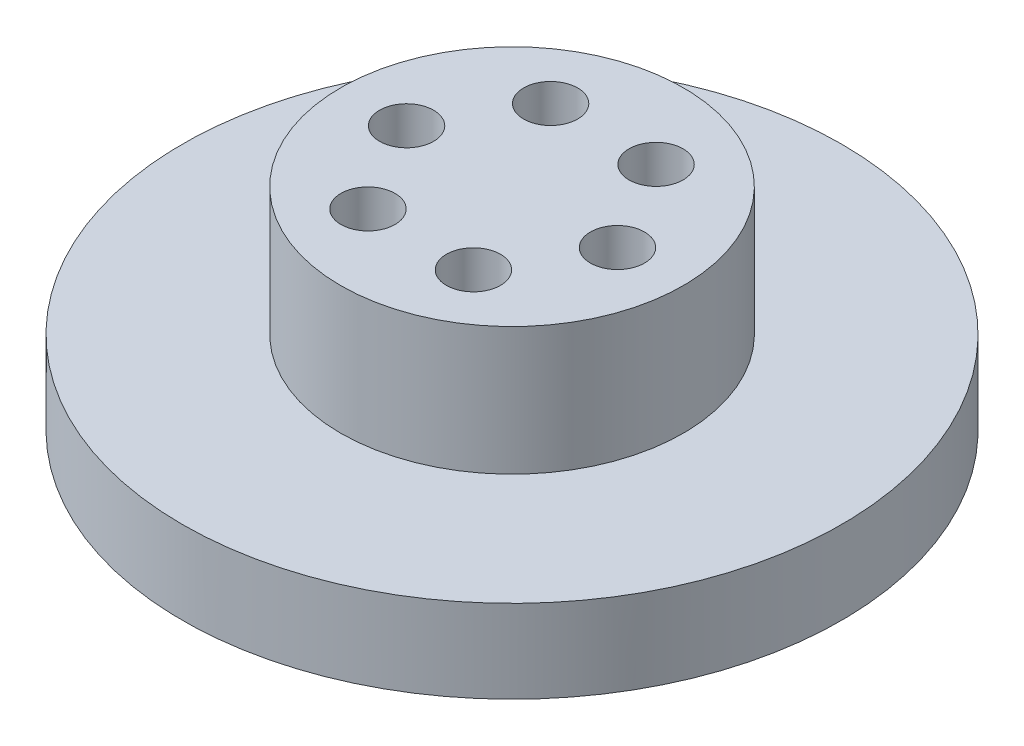
SolidWorks part; units mm, degrees
ref_plane "Front Plane" through (0, 0, 0) normal (0, 0, 1) x (1, 0, 0)
ref_plane "Top Plane" through (0, 0, 0) normal (0, 1, 0) x (1, 0, 0)
ref_plane "Right Plane" through (0, 0, 0) normal (1, 0, 0) x (0, 0, -1)
sketch "Sketch1" plane through (0, 0, 0) normal (0, 1, 0) x (1, 0, 0)
  circle A0 centre (0, 0) radius 16
  circle A2 centre (0, 0) radius 25
  circle A3 centre (16, 0) radius 3.75
  dimension "D1" = 32
  dimension "D3" = 50
  dimension "D4" = 7.5
extrude "Boss-Extrude1" add sketch "Sketch1" along normal blind 8 contours A2
sketch "Sketch2" plane through (0, 8, 0) normal (0, 1, 0) x (1, 0, 0)
  circle A0 centre (0, 0) radius 8
  circle A1 centre (8, 0) radius 2.05
  dimension "D1" = 16
  dimension "D2" = 4.1
extrude "Cut-Extrude3" cut sketch "Sketch2" against normal blind 7 contours A1
pattern_circular "CirPattern2" count 6 over 360 about axis through (0, 0, 0) along (0, 1, 0) of "Cut-Extrude3"
sketch "Sketch3" plane through (0, 0, 0) normal (0, 0, 1) x (1, 0, 0)
  line L0 (25, 6) -> (13, 6)
  line L2 (13, 6) -> (13, 8)
  line L3 (25, 8) -> (-25, 8) construction
  line L4 (13, 8) -> (25, 8)
  line L5 (25, 8) -> (25, 6)
  dimension "D1" = 2
  dimension "D2" = 12
ref_axis "Axis1" through (0, 10.5, 0) along (0, -1, 0)
revolve "Cut-Revolve1" cut sketch "Sketch3" angle 360 about axis through (0, 10.5, 0) along (0, -1, 0)
sketch "Sketch4" plane through (0, 0, 0) normal (0, -1, 0) x (1, 0, 0)
  circle A1 centre (0, 0) radius 25
  circle A2 centre (0, 0) radius 25
  dimension "D1" = 0
extrude "Cut-Extrude4" cut sketch "Sketch4" against normal blind 0.2
sketch "Sketch5" plane through (0, 8, 0) normal (0, 1, 0) x (1, 0, 0)
  circle A0 centre (4, 6.9282) radius 2.05 construction
  circle A1 centre (0, 0) radius 13
  circle A3 centre (8, 0) radius 2.05 construction
  circle A4 centre (4, -6.9282) radius 2.05 construction
  circle A5 centre (-4, -6.9282) radius 2.05 construction
  circle A6 centre (-8, 0) radius 2.05 construction
  circle A7 centre (-4, 6.9282) radius 2.05 construction
  circle A8 centre (4, 6.9282) radius 2.05
  circle A9 centre (8, 0) radius 2.05
  circle A10 centre (4, -6.9282) radius 2.05
  circle A11 centre (-4, -6.9282) radius 2.05
  circle A12 centre (-8, 0) radius 2.05
  circle A13 centre (-4, 6.9282) radius 2.05
  circle A15 centre (0, 0) radius 13
  dimension "D1" = 0
extrude "Boss-Extrude2" add sketch "Sketch5" along normal blind 2.2
sketch "Sketch6" plane through (0, 0.2, 0) normal (0, -1, 0) x (1, 0, 0)
  circle A0 centre (0, 0) radius 3.5
  dimension "D1" = 7
extrude "Cut-Extrude5" cut sketch "Sketch6" against normal blind 9
sketch "Sketch8" plane through (0, 10.2, 0) normal (0, 1, 0) x (1, 0, 0)
  circle A1 centre (4, 6.9282) radius 2.05
  circle A2 centre (4, 6.9282) radius 2.05
  circle A3 centre (8, 0) radius 2.05
  circle A4 centre (8, 0) radius 2.05
  circle A5 centre (4, -6.9282) radius 2.05
  circle A6 centre (4, -6.9282) radius 2.05
  circle A7 centre (-4, -6.9282) radius 2.05
  circle A8 centre (-4, -6.9282) radius 2.05
  circle A9 centre (-8, 0) radius 2.05
  circle A10 centre (-8, 0) radius 2.05
  circle A11 centre (-4, 6.9282) radius 2.05
  circle A12 centre (-4, 6.9282) radius 2.05
  circle M7 centre (-8, 0) radius 2.05
  circle M8 centre (4, -6.9282) radius 2.05
  circle M9 centre (4, 6.9282) radius 2.05
  circle M10 centre (0, 0) radius 13
  circle M11 centre (8, 0) radius 2.05
  circle M12 centre (-4, -6.9282) radius 2.05
  circle M13 centre (-4, 6.9282) radius 2.05
  dimension "D1" = 0
  dimension "D2" = 0
  dimension "D3" = 0
  dimension "D4" = 0
  dimension "D5" = 0
  dimension "D6" = 0
extrude "Boss-Extrude4" add sketch "Sketch8" along normal blind 3 contours M10 M8 M12 M13 M11 M9 M7
sketch "Sketch9" plane through (0, 0.2, 0) normal (0, -1, 0) x (1, 0, 0)
  circle A0 centre (16, 0) radius 3.6
  dimension "D1" = 7.2
  dimension "D2" = 16
extrude "Cut-Extrude6" cut sketch "Sketch9" against normal blind 4 contours A0
pattern_circular "CirPattern3" count 8 over 360 about axis through (0, 0, 0) along (0, 1, 0) of "Cut-Extrude6"
sketch "Sketch11" plane through (0, 0.2, 0) normal (0, -1, 0) x (1, 0, 0)
  circle A0 centre (-16, 0) radius 3.6 construction
  circle A1 centre (-11.3137, -11.3137) radius 3.6 construction
  circle A2 centre (0, -16) radius 3.6 construction
  circle A3 centre (11.3137, -11.3137) radius 3.6 construction
  circle A4 centre (0, 0) radius 3.5 construction
  circle A5 centre (16, 0) radius 3.6 construction
  circle A6 centre (11.3137, 11.3137) radius 3.6 construction
  circle A7 centre (0, 16) radius 3.6 construction
  circle A8 centre (-11.3137, 11.3137) radius 3.6 construction
  circle A9 centre (0, 0) radius 25 construction
  circle A10 centre (-16, 0) radius 3.6
  circle A11 centre (-11.3137, -11.3137) radius 3.6
  circle A12 centre (0, -16) radius 3.6
  circle A13 centre (11.3137, -11.3137) radius 3.6
  circle A14 centre (0, 0) radius 3.5
  circle A15 centre (16, 0) radius 3.6
  circle A16 centre (11.3137, 11.3137) radius 3.6
  circle A17 centre (0, 16) radius 3.6
  circle A18 centre (-11.3137, 11.3137) radius 3.6
  circle A19 centre (0, 0) radius 25
extrude "Boss-Extrude6" add sketch "Sketch11" along normal blind 0.5
sketch "Sketch12" plane through (0, 13.2, 0) normal (0, 1, 0) x (1, 0, 0)
  circle A0 centre (4, 6.9282) radius 2.05 construction
  circle A1 centre (8, 0) radius 2.05 construction
  circle A2 centre (4, -6.9282) radius 2.05 construction
  circle A3 centre (-4, -6.9282) radius 2.05 construction
  circle A4 centre (-8, 0) radius 2.05 construction
  circle A5 centre (-4, 6.9282) radius 2.05 construction
  circle A6 centre (0, 0) radius 13 construction
  circle A7 centre (4, 6.9282) radius 2.05
  circle A8 centre (8, 0) radius 2.05
  circle A9 centre (4, -6.9282) radius 2.05
  circle A10 centre (-4, -6.9282) radius 2.05
  circle A11 centre (-8, 0) radius 2.05
  circle A12 centre (-4, 6.9282) radius 2.05
  circle A13 centre (0, 0) radius 13
extrude "Boss-Extrude7" add sketch "Sketch12" along normal blind 2.5
